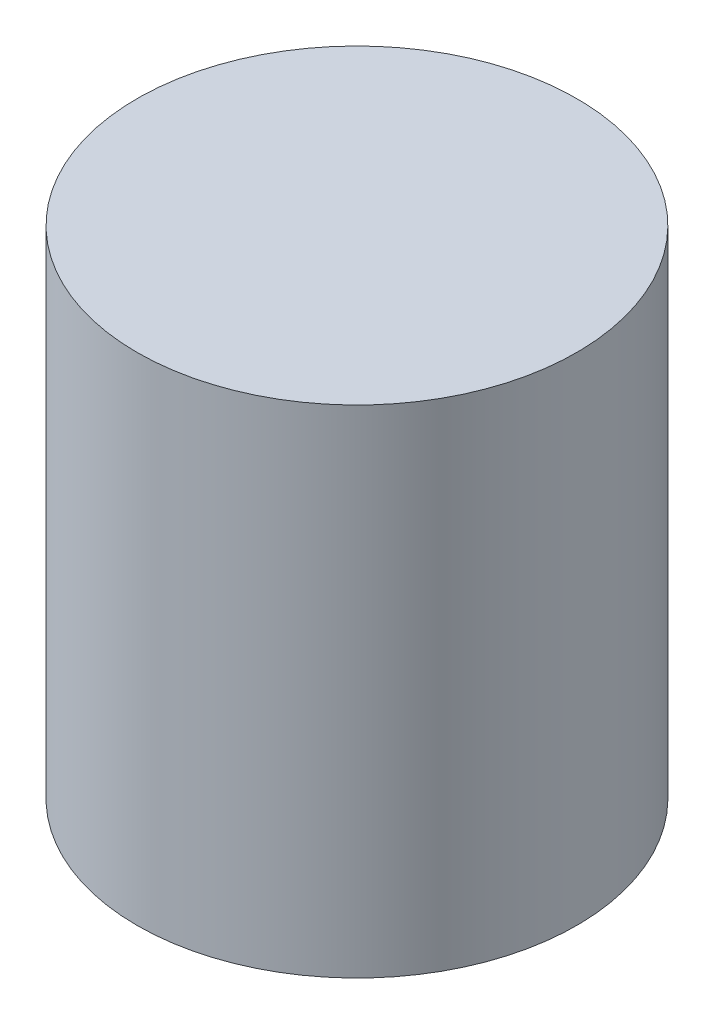
SolidWorks part; units mm, degrees
ref_plane "Plan de face" through (0, 0, 0) normal (0, 0, 1) x (1, 0, 0)
ref_plane "Plan de dessus" through (0, 0, 0) normal (0, 1, 0) x (1, 0, 0)
ref_plane "Plan de droite" through (0, 0, 0) normal (1, 0, 0) x (0, 0, -1)
sketch "Esquisse1" plane through (0, 0, 0) normal (0, 1, 0) x (1, 0, 0)
  circle A0 centre (0, 0) radius 1.75
  dimension "D1" = 3.5
extrude "Boss.-Extru.1" add sketch "Esquisse1" along normal blind 3.95
